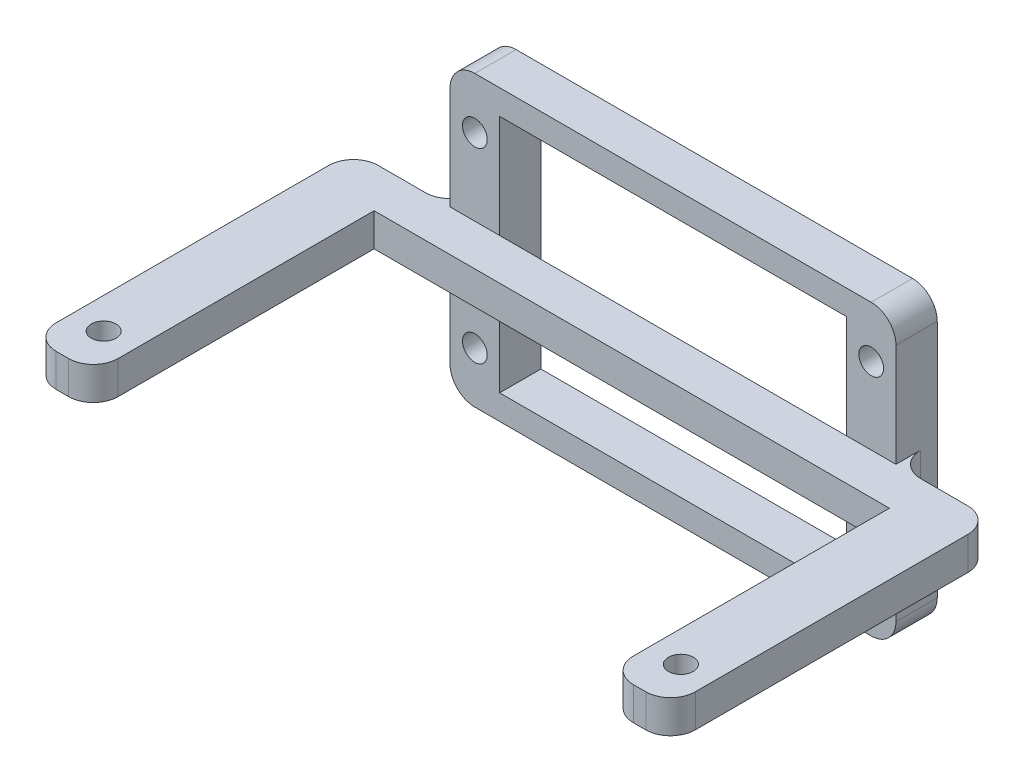
SolidWorks part; units mm, degrees
ref_plane "前视基准面" through (0, 0, 0) normal (0, 0, 1) x (1, 0, 0)
ref_plane "上视基准面" through (0, 0, 0) normal (0, 1, 0) x (1, 0, 0)
ref_plane "右视基准面" through (0, 0, 0) normal (1, 0, 0) x (0, 0, -1)
other "Configuration Table"
sketch "草图1" plane through (0, 0, 0) normal (0, 1, 0) x (1, 0, 0)
  line L0 (31.2, 0) -> (-31.2, 0)
  line L1 (-31.2, 0) -> (-31.2, -34)
  line L2 (-31.2, -34) -> (-38.7, -34)
  line L3 (-38.7, -34) -> (-38.7, 5)
  line L4 (-38.7, 5) -> (38.7, 5)
  line L5 (31.2, 0) -> (31.2, -34)
  line L6 (38.7, -34) -> (38.7, 5)
  line L7 (31.2, -34) -> (38.7, -34)
  line L8 (0, 0) -> (0, 5)
  line L9 (-34.95, -34) -> (-34.95, 49966) construction
  circle A0 centre (-34.95, -29) radius 1.5
  circle A1 centre (34.95, -29) radius 1.5
  point P13 (-34.95, -34)
  dimension "D4" = 3
  dimension "D1" = 77.4
  dimension "D2" = 62.4
  dimension "D3" = 34
  dimension "D5" = 5
  dimension "D6" = 5
extrude "凸台-拉伸1" add sketch "草图1" along normal blind 4 contours L8 L0 L5 L7 L6 L4 A1 | L9 L2 L1 L0 L8 L4 A0 | L2 L9 A0 L4 L3
sketch "草图3" plane through (0, 0, -5) normal (0, 0, -1) x (-1, 0, 0)
  line L0 (-40.7, 2) -> (-50040.7, 2) construction
  line L1 (-27, 2) -> (-27, -12.5)
  line L2 (38.7, 0) -> (-38.7, 0) construction
  line L3 (0, 0) -> (0, -50000) construction
  line L4 (-21, -12.5) -> (21, -12.5)
  line L5 (-27, 2) -> (-27, 16.5)
  line L6 (-21, 16.5) -> (21, 16.5)
  line L7 (-21, -12.5) -> (0, -12.5)
  line L8 (-21, 16.5) -> (0, 16.5)
  line L9 (27, 2) -> (27, -12.5)
  line L10 (27, 2) -> (27, 16.5)
  line L11 (-27, 16.5) -> (-27, 19.5)
  line L12 (-27, 19.5) -> (27, 19.5)
  line L13 (27, 19.5) -> (27, 16.5)
  line L14 (-27, -12.5) -> (-27, -15.5)
  line L15 (-27, -15.5) -> (27, -15.5)
  line L16 (27, -15.5) -> (27, -12.5)
  line L17 (-21, 16.5) -> (-21, -12.5)
  line L18 (21, 16.5) -> (21, -12.5)
  circle A0 centre (-24, 13.3) radius 1.5
  circle A1 centre (24, 13.3) radius 1.5
  circle A2 centre (24, -9.3) radius 1.5
  circle A3 centre (-24, -9.3) radius 1.5
  line M12 (-38.7, 0) -> (38.7, 0)
  line M14 (38.7, 4) -> (-38.7, 4)
  dimension "D7" = 3
  dimension "D1" = 2
  dimension "D2" = 54
  dimension "D3" = 29
  dimension "D4" = 42
  dimension "D5" = 3
  dimension "D6" = 3
  dimension "D8" = 3.2
extrude "凸台-拉伸2" add sketch "草图3" along normal blind 5 contours L18 L4 L17 L1 L14 L15 L16 L9 M12 | L17 L5 L1 M14 M12 | L6 L18 L10 L13 L12 L11 L5 L17 A0 A1 M14 | L18 L9 L10 M14 M12
fillet "圆角1" radius 3 8 edges at (27, -15.5, -7.5) (27, 19.5, -7.5) (-27, -15.5, -7.5) (-38.7, 2, -5) (-27, 19.5, -7.5) (-27, 2, -5) (38.7, 2, -5) (27, 2, -5)
fillet "圆角2" radius 3 4 edges at (38.7, 2, 34) (31.2, 2, 34) (-31.2, 2, 34) (-38.7, 2, 34)
